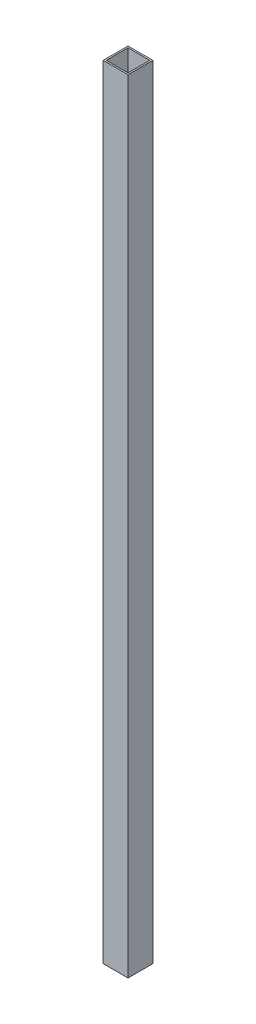
SolidWorks part; units mm, degrees
ref_plane "Front Plane" through (0, 0, 0) normal (0, 0, 1) x (1, 0, 0)
ref_plane "Top Plane" through (0, 0, 0) normal (0, 1, 0) x (1, 0, 0)
ref_plane "Right Plane" through (0, 0, 0) normal (1, 0, 0) x (0, 0, -1)
sketch "Sketch1" plane through (0, 0, 0) normal (0, 1, 0) x (1, 0, 0)
  line L1 (12.7, -12.7) -> (-12.7, -12.7)
  line L2 (12.7, -12.7) -> (12.7, 12.7)
  line L3 (12.7, 12.7) -> (-12.7, 12.7)
  line L4 (-12.7, -12.7) -> (-12.7, 12.7)
  line L5 (12.7, -12.7) -> (-12.7, 12.7) construction
  line L6 (12.7, 12.7) -> (-12.7, -12.7) construction
  line L7 (11.1125, -11.1125) -> (-11.1125, -11.1125)
  line L8 (11.1125, -11.1125) -> (11.1125, 11.1125)
  line L9 (11.1125, 11.1125) -> (-11.1125, 11.1125)
  line L10 (-11.1125, -11.1125) -> (-11.1125, 11.1125)
  line L11 (11.1125, -11.1125) -> (-11.1125, 11.1125) construction
  line L12 (11.1125, 11.1125) -> (-11.1125, -11.1125) construction
  point P0 (0, 0)
  point P6 (0, 0)
  dimension "D1" = 25.4
  dimension "D2" = 25.4
  dimension "D3" = 1.5875
extrude "Boss-Extrude2" add sketch "Sketch1" along normal blind 800.1
